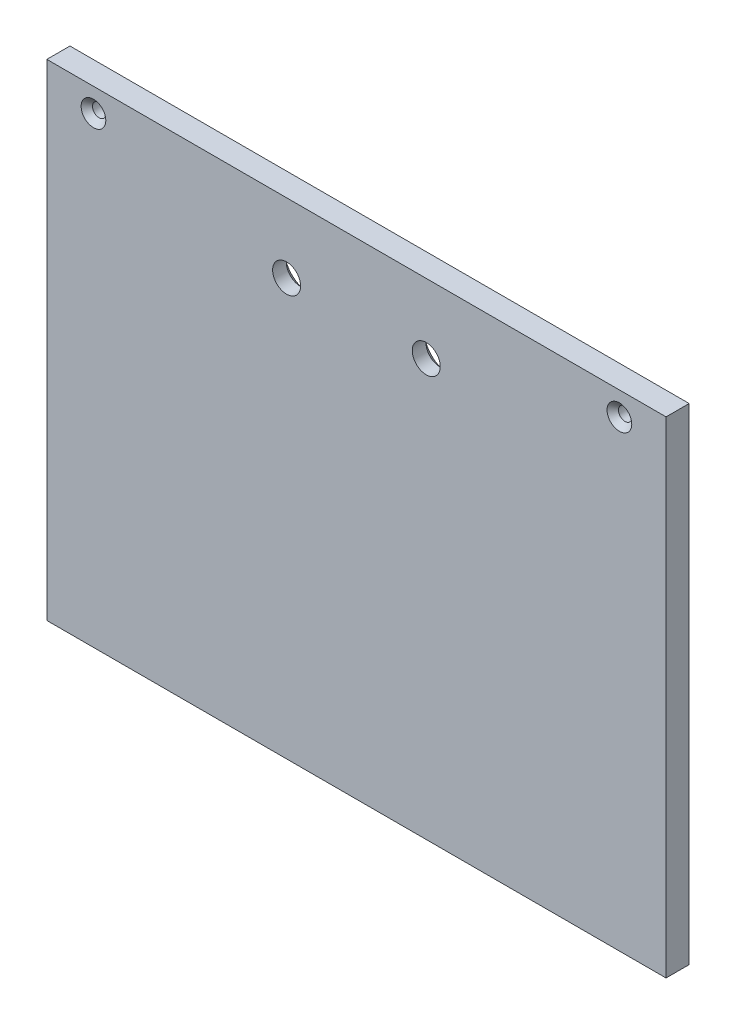
SolidWorks part; units mm, degrees
material "Acrylic (Medium-high impact)"
ref_plane "Front Plane" through (0, 0, 0) normal (0, 0, 1) x (1, 0, 0)
ref_plane "Top Plane" through (0, 0, 0) normal (0, 1, 0) x (1, 0, 0)
ref_plane "Right Plane" through (0, 0, 0) normal (1, 0, 0) x (0, 0, -1)
sketch "Sketch1" plane through (0, 0, 0) normal (0, 0, 1) x (1, 0, 0)
  line L1 (-79, 62) -> (79, 62)
  line L2 (-79, 62) -> (-79, -62)
  line L3 (-79, -62) -> (79, -62)
  line L4 (79, 62) -> (79, -62)
  line L5 (-79, 62) -> (79, -62) construction
  line L6 (-79, -62) -> (79, 62) construction
  point P0 (0, 0)
  dimension "D1" = 158
  dimension "D2" = 124
extrude "Boss-Extrude1" add sketch "Sketch1" along normal blind 5.9
hole_wizard "CSK for M3 Flat Head Machine Screw1" positions "Sketch2" profile "Sketch3" countersink size "M3" standard "ANSI Metric"
sketch "Sketch2" plane through (0, 0, 5.9) normal (0, 0, 1) x (1, 0, 0)
  point P0 (-67.1, 56)
  point P3 (67.1, 56)
sketch "Sketch3" plane through (-67.1, 56, 5.9) normal (1, 0, 0) x (0, -1, 0)
  line L0 (0, 0) -> (0, 11.0215)
  line L1 (0, 11.0215) -> (1.7, 10)
  line L2 (1.7, 10) -> (1.7, 1.45)
  line L3 (1.7, 1.45) -> (3.15, 0)
  line L5 (3.15, 0) -> (0, 0)
  line L6 (-1.7, 1.45) -> (-3.15, 0) construction
  line L10 (0, 11.0215) -> (-1.7, 10) construction
  line L11 (0, -6.35) -> (0, 107.95) construction
  dimension "Hole Dia." = 3.4
  dimension "Hole Depth" = 10
  dimension "Near C'Sink Dia." = 6.3
  dimension "Near C'Sink Angle" = 90
  dimension "Drill Angle" = 118
hole_wizard "CSK for 1/4 Flat Head Machine Screw (100)1" positions "Sketch10" profile "Sketch11" countersink size "1/4" standard "ANSI Inch" end condition through all
sketch "Sketch10" plane through (0, 0, 0) normal (0, 0, 1) x (1, 0, 0)
  point P0 (-17.8187, 44.2682)
  point P3 (17.8188, 44.2682)
sketch "Sketch11" plane through (-17.8187, 44.2682, 0) normal (1, 0, 0) x (0, 1, 0)
  line L0 (0, 0) -> (0, 5.9)
  line L1 (0, 5.9) -> (3.5712, 5.9)
  line L2 (3.5712, 5.9) -> (3.5712, 2.4063)
  line L3 (3.5712, 2.4063) -> (6.4389, 0)
  line L5 (6.4389, 0) -> (0, 0)
  line L6 (-3.5712, 2.4063) -> (-6.4389, 0) construction
  line L11 (0, -6.35) -> (0, 107.95) construction
  dimension "Thru Hole Dia." = 7.1425
  dimension "Thru Hole Depth" = 5.9
  dimension "Near C'Sink Dia." = 12.8778
  dimension "Near C'Sink Angle" = 100
hole_wizard "CSK for #4 Flat Head Machine Screw (100)2" positions "Sketch14" profile "Sketch15" countersink size "#4" standard "ANSI Inch"
sketch "Sketch14" plane through (0, 0, 0) normal (0, 0, -1) x (-1, 0, 0)
  point P0 (-65, -57)
  point P3 (65, -57)
sketch "Sketch15" plane through (65, -57, 0) normal (1, 0, 0) x (0, 1, 0)
  line L0 (0, 0) -> (0, 10.9806)
  line L1 (0, 10.9806) -> (1.6319, 10)
  line L2 (1.6319, 10) -> (1.6319, 1.0284)
  line L3 (1.6319, 1.0284) -> (2.8575, 0)
  line L5 (2.8575, 0) -> (0, 0)
  line L6 (-1.6319, 1.0284) -> (-2.8575, 0) construction
  line L10 (0, 10.9806) -> (-1.6319, 10) construction
  line L11 (0, -6.35) -> (0, 107.95) construction
  dimension "Hole Dia." = 3.2639
  dimension "Hole Depth" = 10
  dimension "Near C'Sink Dia." = 5.715
  dimension "Near C'Sink Angle" = 100
  dimension "Drill Angle" = 118
